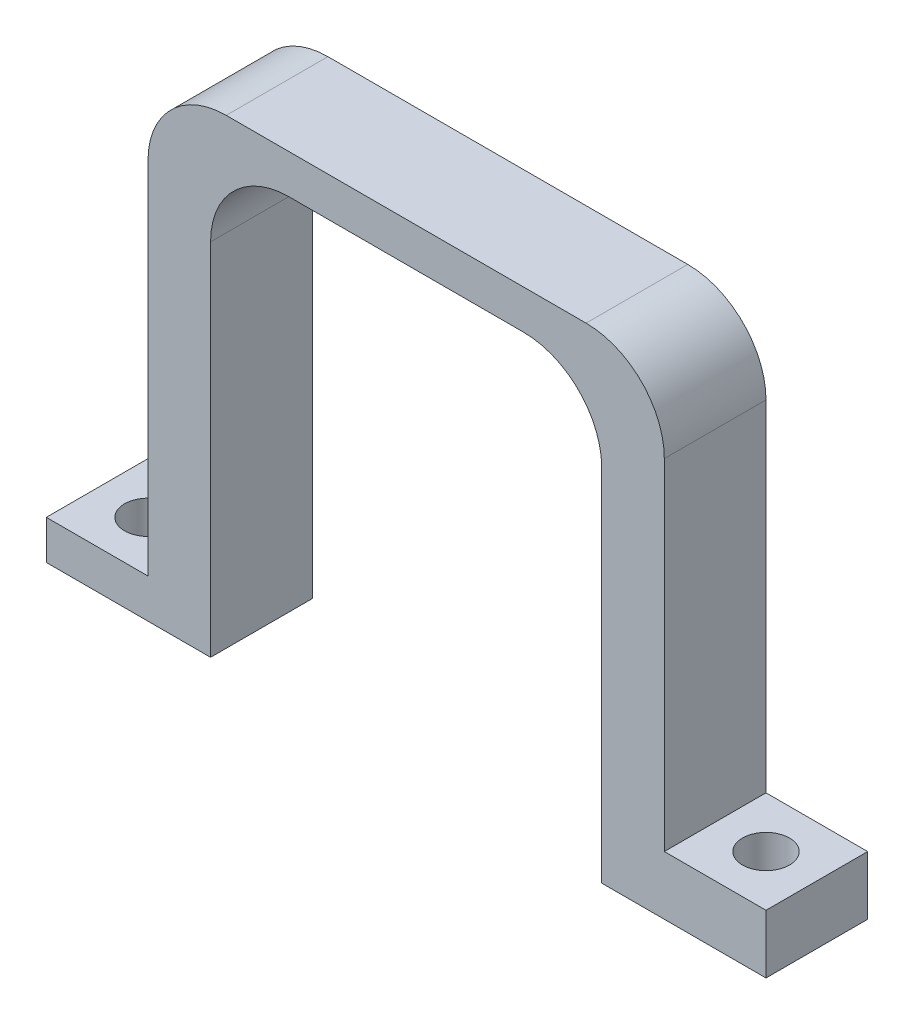
SolidWorks part; units mm, degrees
ref_plane "前视基准面" through (0, 0, 0) normal (0, 0, 1) x (1, 0, 0)
ref_plane "上视基准面" through (0, 0, 0) normal (0, 1, 0) x (1, 0, 0)
ref_plane "右视基准面" through (0, 0, 0) normal (1, 0, 0) x (0, 0, -1)
other "Configuration Table"
sketch "草图1" plane through (0, 0, 0) normal (0, 0, 1) x (1, 0, 0)
  line L1 (-6.6, 6.1) -> (6.6, 6.1)
  line L2 (-6.6, 6.1) -> (-6.6, -6.1)
  line L3 (-6.6, -6.1) -> (6.6, -6.1)
  line L4 (6.6, 6.1) -> (6.6, -6.1)
  line L9 (-5, 5.1) -> (5, 5.1)
  line L10 (-5, 5.1) -> (-5, -6.1)
  line L11 (-5, -6.1) -> (5, -6.1)
  line L12 (5, 5.1) -> (5, -6.1)
  point P5 (6.6, 0)
  point P7 (0, -6.1)
  point P11 (0, 5.1)
  dimension "D3" = 10
  dimension "D1" = 13.2
  dimension "D2" = 12.2
  dimension "D4" = 11.2
extrude "凸台-拉伸1" add sketch "草图1" along normal blind 2.6 contours L3 L4 L1 L2 | L10 L11 L12 L9
fillet "圆角1" radius 2 4 edges at (-6.6, 6.1, 1.3) (6.6, 6.1, 1.3) (-5, 5.1, 1.3) (5, 5.1, 1.3)
sketch "草图2" plane through (0, -6.1, 0) normal (0, -1, 0) x (1, 0, 0)
  line L0 (-6.6, 2.6) -> (-5, 2.6) construction
  line L1 (-6.6, 0) -> (-9.2, 0)
  line L2 (-6.6, 0) -> (-6.6, 2.6)
  line L3 (-6.6, 2.6) -> (-9.2, 2.6)
  line L4 (-9.2, 0) -> (-9.2, 2.6)
  line L5 (6.6, 0) -> (9.2, 0)
  line L6 (6.6, 0) -> (6.6, 2.6)
  line L7 (6.6, 2.6) -> (9.2, 2.6)
  line L8 (9.2, 0) -> (9.2, 2.6)
  line L9 (-6.6, 4.35) -> (-6.6, 2.6) construction
  circle A0 centre (-7.9, 1.3) radius 0.6
  circle A1 centre (7.9, 1.3) radius 0.6
  point P18 (6.6, 2.6)
  point P20 (0, 0)
  point P21 (7.9, 2.6)
  point P22 (0, 0)
  point P23 (9.2, 1.3)
  point P24 (0, 0)
  point P25 (0, 0)
  point P26 (-7.9, 2.6)
  line M6 (-6.6, 2.6) -> (-6.6, 0)
  dimension "D1" = 1.2
extrude "凸台-拉伸2" add sketch "草图2" against normal blind 1.5 contours L4 L1 L3 A0 M6 | L5 L8 L7 L6 A1
sketch "草图3" plane through (0, 0, 0) normal (0, 0, -1) x (-1, 0, 0)
  line L0 (9.2, -4.6) -> (9.2, -6.1) construction
  line L1 (6.6, -4.6) -> (9.2, -4.6)
  line L2 (6.6, -4.6) -> (6.6, -5.1)
  line L3 (6.6, -5.1) -> (9.2, -5.1)
  line L4 (9.2, -4.6) -> (9.2, -5.1)
  dimension "D1" = 0.5
extrude "切除-拉伸1" cut sketch "草图3" against normal through all
